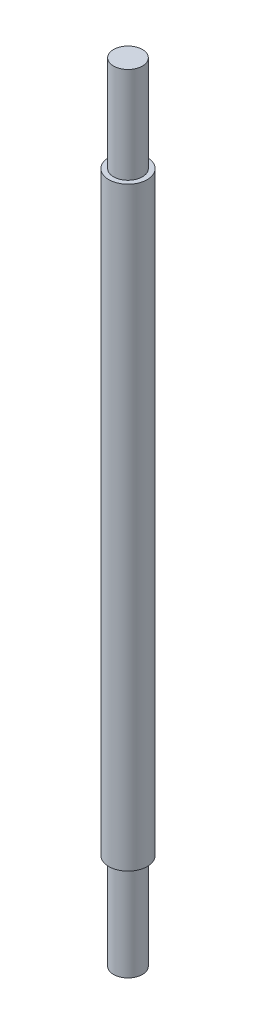
SolidWorks part; units mm, degrees
material "Polyetheretherketone (PEEK)"
ref_plane "Front Plane" through (0, 0, 0) normal (0, 0, 1) x (1, 0, 0)
ref_plane "Top Plane" through (0, 0, 0) normal (0, 1, 0) x (1, 0, 0)
ref_plane "Right Plane" through (0, 0, 0) normal (1, 0, 0) x (0, 0, -1)
sketch "Sketch1" plane through (0, 0, 0) normal (0, 1, 0) x (1, 0, 0)
  circle A0 centre (0, 0) radius 2
  dimension "D1" = 4
extrude "Boss-Extrude1" add sketch "Sketch1" along normal blind 62
sketch "Sketch2" plane through (0, 62, 0) normal (0, 1, 0) x (1, 0, 0)
  circle A0 centre (0, 0) radius 1.5
  dimension "D1" = 3
extrude "Boss-Extrude2" add sketch "Sketch2" along normal blind 10
sketch "Sketch3" plane through (0, 0, 0) normal (0, -1, 0) x (1, 0, 0)
  circle A0 centre (0, 0) radius 1.5
  dimension "D1" = 3
extrude "Boss-Extrude3" add sketch "Sketch3" along normal blind 10
